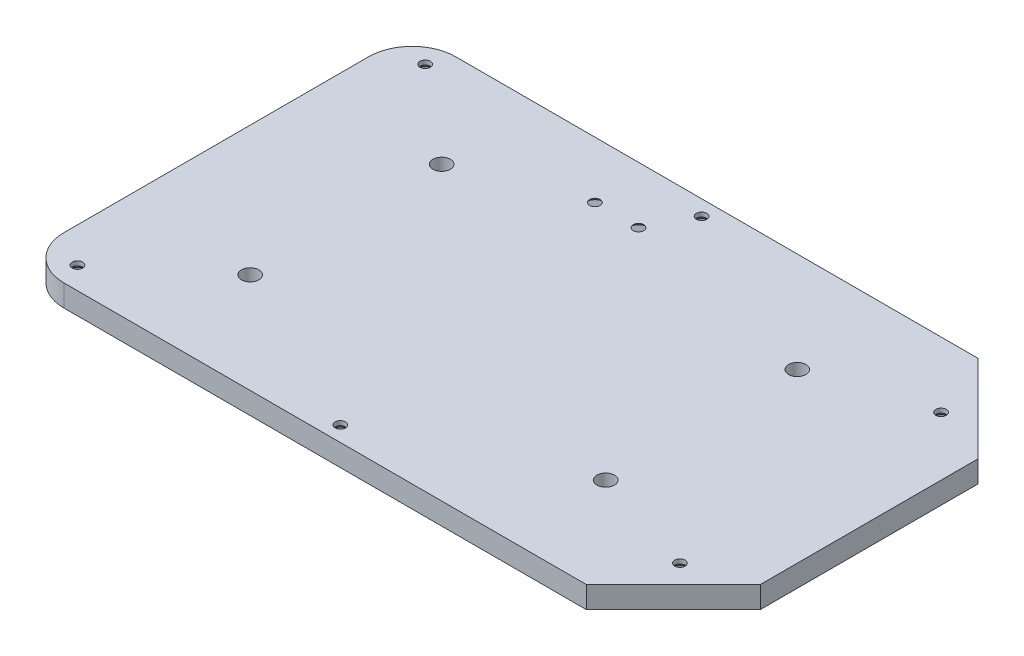
SolidWorks part; units mm, degrees
ref_plane "Piano frontale" through (0, 0, 0) normal (0, 0, 1) x (1, 0, 0)
ref_plane "Piano superiore" through (0, 0, 0) normal (0, 1, 0) x (1, 0, 0)
ref_plane "Piano destro" through (0, 0, 0) normal (1, 0, 0) x (0, 0, -1)
sketch "Schizzo1" plane through (0, 0, 0) normal (0, 1, 0) x (1, 0, 0)
  line L0 (-29.167, 45) -> (90.833, 45)
  line L1 (90.833, 45) -> (110.833, 25)
  line L2 (110.833, 25) -> (110.833, -25)
  line L3 (110.833, -25) -> (90.833, -45)
  line L4 (90.833, -45) -> (-29.167, -45)
  line L5 (-39.167, -35) -> (-39.167, 35)
  line L6 (-69.7849, 0) -> (101.8116, 0) construction
  arc A0 (-29.167, -45) -> (-39.167, -35) centre (-29.167, -35) cw
  arc A1 (-29.167, 45) -> (-39.167, 35) centre (-29.167, 35) ccw
  point P15 (110.833, 0)
  point P16 (-39.167, 0)
  dimension "D1" = 10
  dimension "D2" = 90
  dimension "D3" = 120
  dimension "D4" = 150
  dimension "D5" = 50
extrude "Estrusione-Estrusione1" add sketch "Schizzo1" along normal blind 5
sketch "Schizzo2" plane through (0, 0, 0) normal (0, -1, 0) x (1, 0, 0)
  line L0 (90.833, -45) -> (-29.167, -45) construction
  line L1 (10.833, -29) -> (30.833, -29)
  line L2 (10.833, -29) -> (10.833, -35)
  line L3 (10.833, -35) -> (30.833, -35)
  line L4 (30.833, -29) -> (30.833, -35)
  line L5 (10.833, -29) -> (30.833, -35) construction
  line L6 (10.833, -35) -> (30.833, -29) construction
  line L7 (-39.167, -35) -> (-39.167, 35) construction
  point P0 (20.833, -32)
  dimension "D1" = 6
  dimension "D2" = 20
  dimension "D3" = 10
  dimension "D4" = 50
extrude "Taglio-Estrusione1" cut sketch "Schizzo2" against normal blind 4
hole_wizard "Foro svasato per Vite M2-1" positions "Schizzo4" profile "Schizzo5" countersink size "M2" standard "ISO"
sketch "Schizzo4" plane through (0, 4, 0) normal (0, -1, 0) x (-1, 0, 0)
  line L0 (-20.833, 35) -> (-20.833, 29) construction
  line L1 (-10.833, 35) -> (-30.833, 35) construction
  line L2 (-30.833, 29) -> (-10.833, 29) construction
  line L4 (-30.833, 32) -> (-10.833, 32) construction
  line L5 (-30.833, 35) -> (-30.833, 29) construction
  line L6 (-10.833, 29) -> (-10.833, 35) construction
  point P17 (-25.833, 32)
  point P19 (-15.833, 32)
  dimension "D1" = 5
sketch "Schizzo5" plane through (15.833, 4, -32) normal (1, 0, 0) x (0, 0, -1)
  line L0 (0, 0) -> (0, 4)
  line L1 (0, 4) -> (1.2, 4)
  line L2 (1.2, 4) -> (1.2, 1)
  line L3 (1.2, 1) -> (2.2, 0)
  line L5 (2.2, 0) -> (0, 0)
  line L6 (-1.2, 1) -> (-2.2, 0) construction
  line L10 (0, 4) -> (-1.2, 4) construction
  line L11 (0, -6.35) -> (0, 107.95) construction
  dimension "Hole Dia." = 2.4
  dimension "Hole Depth" = 4
  dimension "Near C'Sink Dia." = 4.4
  dimension "Near C'Sink Angle" = 90
  dimension "Drill Angle" = 180
sketch "Schizzo6" plane through (0, 0, 0) normal (0, -1, 0) x (1, 0, 0)
  line L0 (-25.377, 38) -> (-25.377, -38) construction
  line L1 (-25.377, 38) -> (88.303, 38)
  line L2 (-39.167, -35) -> (-39.167, 35) construction
  line L3 (-29.167, 45) -> (90.833, 45) construction
  line L5 (31.463, 38) -> (31.463, -41.8967) construction
  line L6 (-25.377, 0) -> (94.6836, 0) construction
  circle A0 centre (-9.377, 22) radius 2
  circle A1 centre (72.303, 22) radius 2
  circle A2 centre (72.303, -22) radius 2
  circle A3 centre (-9.377, -22) radius 2
  dimension "D3" = 4
  dimension "D1" = 13.79
  dimension "D2" = 7
  dimension "D4" = 16
  dimension "D5" = 16
  dimension "D6" = 113.68
  dimension "D7" = 76
extrude "Taglio-Estrusione3" cut sketch "Schizzo6" against normal blind 38 contours A1 | A0 | A2 | A3
sketch "Schizzo8" plane through (0, 0, 0) normal (0, -1, 0) x (1, 0, 0)
  line L0 (-39.167, -35) -> (-39.167, 35) construction
  line L1 (-29.167, 45) -> (90.833, 45) construction
  line L2 (90.833, -45) -> (-29.167, -45) construction
  line L3 (110.833, -25) -> (90.833, -45) construction
  line L4 (90.833, 45) -> (110.833, 25) construction
  line L5 (-39.167, 0) -> (110.833, 0) construction
  line L6 (110.833, 25) -> (110.833, -25) construction
  circle A0 centre (-31.167, 40) radius 3
  circle A1 centre (30.833, 41.5) radius 3
  circle A2 centre (97.3477, 30) radius 3
  circle A3 centre (97.3477, -30) radius 3
  circle A4 centre (30.833, -41.5) radius 3
  circle A5 centre (-31.167, -40) radius 3
  dimension "D13" = 6
  dimension "D14" = 6
  dimension "D15" = 6
  dimension "D16" = 6
  dimension "D17" = 6
  dimension "D18" = 6
  dimension "D1" = 70
  dimension "D2" = 3.5
  dimension "D3" = 3.5
  dimension "D4" = 70
  dimension "D5" = 6
  dimension "D6" = 15
  dimension "D7" = 6
  dimension "D8" = 15
  dimension "D9" = 8
  dimension "D10" = 8
  dimension "D11" = 40
  dimension "D12" = 40
extrude "Taglio-Estrusione4" cut sketch "Schizzo8" against normal blind 3 contours A5 | A4 | A3 | A2 | A1 | A0
hole_wizard "Foro svasato per Vite M2-2" positions "Schizzo9" profile "Schizzo10" countersink size "M2" standard "ISO"
sketch "Schizzo9" plane through (0, 3, 0) normal (0, -1, 0) x (-1, 0, 0)
  point P0 (31.1612, -39.8922)
  point P2 (-30.833, -41.5)
  point P5 (-97.3477, -30)
  point P8 (-97.3477, 30)
  point P11 (-30.833, 41.5)
  point P14 (31.167, 40)
sketch "Schizzo10" plane through (-31.1612, 3, 39.8922) normal (1, 0, 0) x (0, 0, -1)
  line L0 (0, 0) -> (0, 4)
  line L1 (0, 4) -> (1.2, 4)
  line L2 (1.2, 4) -> (1.2, 1)
  line L3 (1.2, 1) -> (2.2, 0)
  line L5 (2.2, 0) -> (0, 0)
  line L6 (-1.2, 1) -> (-2.2, 0) construction
  line L10 (0, 4) -> (-1.2, 4) construction
  line L11 (0, -6.35) -> (0, 107.95) construction
  dimension "Hole Dia." = 2.4
  dimension "Hole Depth" = 4
  dimension "Near C'Sink Dia." = 4.4
  dimension "Near C'Sink Angle" = 90
  dimension "Drill Angle" = 180
